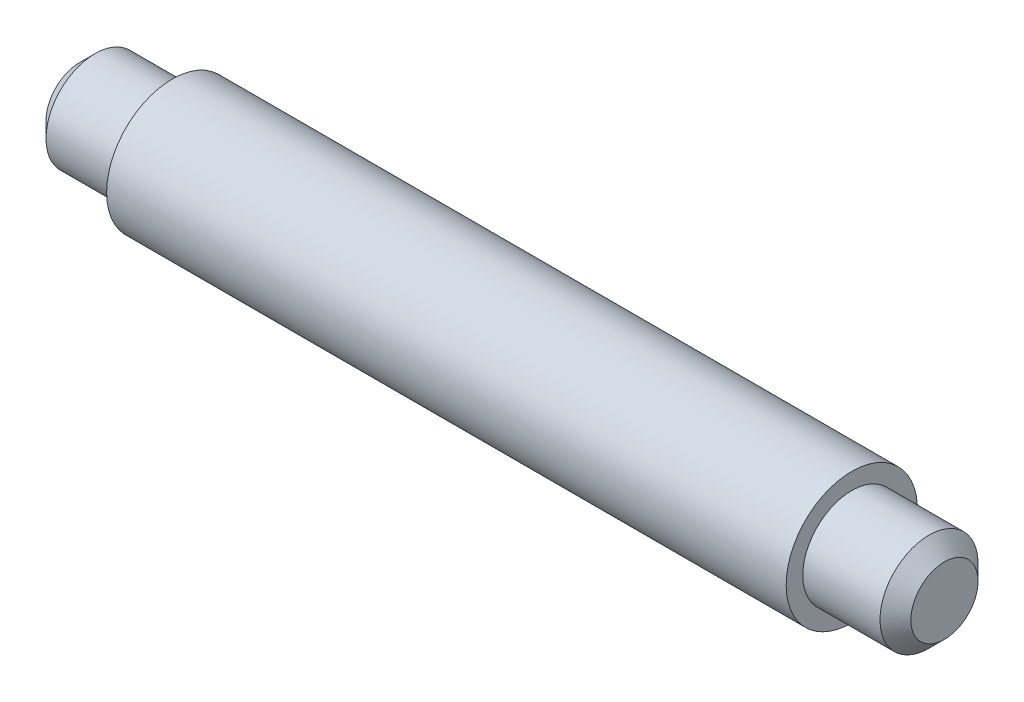
SolidWorks part; units mm, degrees
ref_plane "Front Plane" through (0, 0, 0) normal (0, 0, 1) x (1, 0, 0)
ref_plane "Top Plane" through (0, 0, 0) normal (0, 1, 0) x (1, 0, 0)
ref_plane "Right Plane" through (0, 0, 0) normal (1, 0, 0) x (0, 0, -1)
sketch "Sketch1" plane through (0, 0, 0) normal (0, 0, 1) x (1, 0, 0)
  line L0 (-36.1765, 0) -> (40.1176, 0) construction
  line L1 (-28, 0) -> (-28, 2.175)
  line L2 (-28, 2.175) -> (-27, 3.175)
  line L3 (-27, 3.175) -> (-22, 3.175)
  line L4 (-22, 3.175) -> (-22, 4.25)
  line L5 (-22, 4.25) -> (22, 4.25)
  line L6 (22, 4.25) -> (22, 3.175)
  line L7 (22, 3.175) -> (27, 3.175)
  line L8 (27, 3.175) -> (28, 2.175)
  line L9 (28, 2.175) -> (28, 0)
  line L10 (-28, 0) -> (28, 0)
  dimension "D1" = 1
  dimension "D2" = 45
  dimension "D3" = 6
  dimension "D4" = 3.175
  dimension "D5" = 4.25
  dimension "D6" = 1
  dimension "D7" = 44
  dimension "D8" = 56
  dimension "D9" = 6
  dimension "D10" = 28
revolve "Revolve1" add sketch "Sketch1" angle 360 about L0
